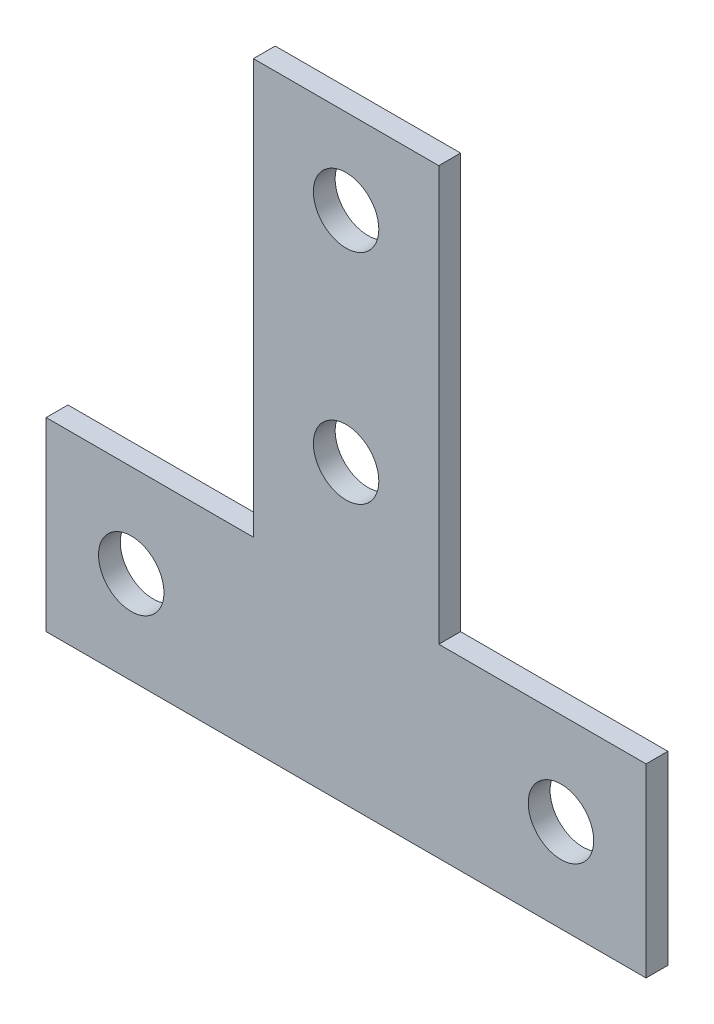
SolidWorks part; units mm, degrees
ref_plane "前视基准面" through (0, 0, 0) normal (0, 0, 1) x (1, 0, 0)
ref_plane "上视基准面" through (0, 0, 0) normal (0, 1, 0) x (1, 0, 0)
ref_plane "右视基准面" through (0, 0, 0) normal (1, 0, 0) x (0, 0, -1)
sketch "草图1" plane through (0, 0, 0) normal (0, 0, 1) x (1, 0, 0)
  line L1 (-27.5, -8.5) -> (27.5, -8.5)
  line L2 (-27.5, -8.5) -> (-27.5, 8.5)
  line L3 (-27.5, 8.5) -> (-8.5, 8.5)
  line L4 (27.5, -8.5) -> (27.5, 8.5)
  line L5 (-27.5, -8.5) -> (27.5, 8.5) construction
  line L6 (-27.5, 8.5) -> (27.5, -8.5) construction
  line L9 (-8.5, 46.5) -> (8.5, 46.5)
  line L10 (8.5, 8.5) -> (27.5, 8.5)
  line L11 (-8.5, 8.5) -> (-8.5, 46.5)
  line L12 (8.5, 8.5) -> (8.5, 46.5)
  point P0 (0, 0)
  point P6 (0, 46.5)
  dimension "D1" = 17
  dimension "D2" = 55
  dimension "D3" = 17
  dimension "D4" = 55
extrude "凸台-拉伸1" add sketch "草图1" along normal blind 2
sketch "草图2" plane through (0, 0, 2) normal (0, 0, 1) x (1, 0, 0)
  line L0 (0, 0) -> (0, 16.8919) construction
  line L2 (-27.5, 8.5) -> (-27.5, -8.5) construction
  line L3 (8.5, 46.5) -> (-8.5, 46.5) construction
  circle A0 centre (0, 38.7) radius 3
  circle A1 centre (0, 18.7) radius 3
  circle A2 centre (-19.7, 0) radius 3
  circle A3 centre (19.7, 0) radius 3
  dimension "D1" = 6
  dimension "D2" = 6
  dimension "D3" = 6
  dimension "D4" = 7.8
  dimension "D5" = 20
  dimension "D6" = 7.8
extrude "切除-拉伸1" cut sketch "草图2" against normal through all
